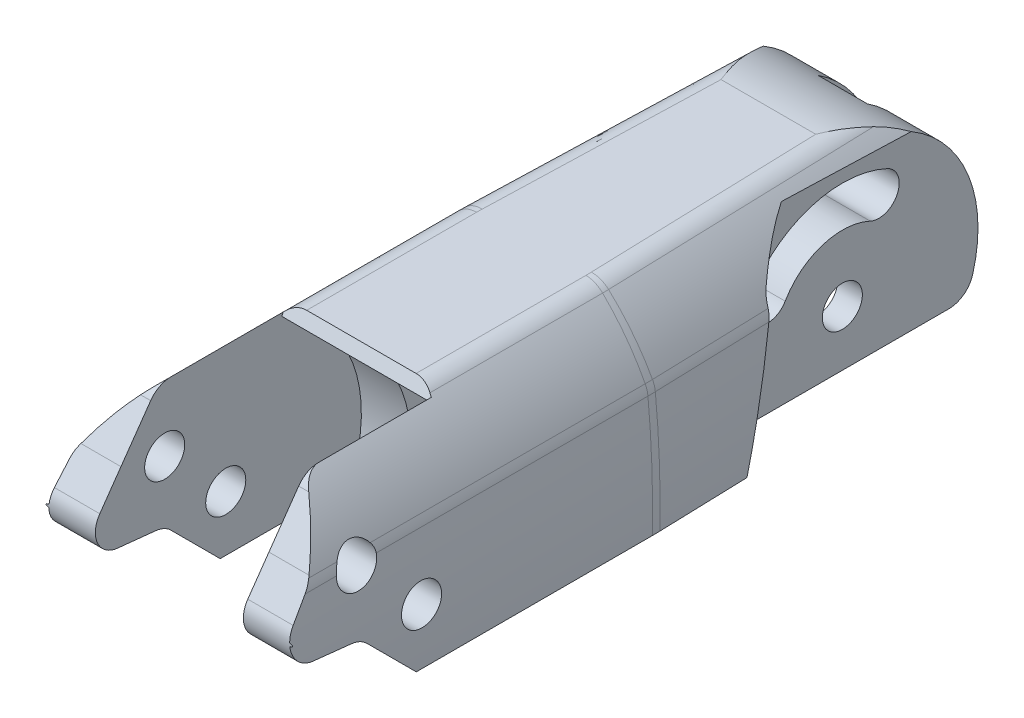
SolidWorks part; units mm, degrees
ref_plane "Front Plane" through (0, 0, 0) normal (0, 0, 1) x (1, 0, 0)
ref_plane "Top Plane" through (0, 0, 0) normal (0, 1, 0) x (1, 0, 0)
ref_plane "Right Plane" through (0, 0, 0) normal (1, 0, 0) x (0, 0, -1)
sketch "Sketch1" plane through (0, 0, 0) normal (1, 0, 0) x (0, 0, -1)
  line L0 (0, 0) -> (-19, 0) construction
  line L1 (-19, 0) -> (-23.9497, 4.9497) construction
  line L2 (19, 11) -> (-22.9449, 11)
  line L3 (-24.5832, 10.1472) -> (-29.2132, 3.5349)
  line L4 (-23.4481, -0.5017) -> (-19.4497, -4.5)
  line L5 (-19.4497, -4.5) -> (27.6458, -4.5)
  line L6 (0, 0) -> (19, 0) construction
  line L7 (19, 0) -> (12.9378, 3.5) construction
  line L8 (21.9583, 6.3442) -> (19, 0) construction
  line L9 (-27.7817, 0.3984) -> (-24.6554, 0.0734)
  circle A0 centre (-19, 0) radius 1.625
  circle A1 centre (19, 0) radius 1.625
  circle A2 centre (-23.9497, 4.9497) radius 1.625
  arc A3 (29.5671, -3.0556) -> (19, 11) centre (19, 0) ccw
  arc A4 (27.6458, -4.5) -> (29.5671, -3.0556) centre (27.6458, -2.5) ccw
  arc A7 (-22.9449, 11) -> (-24.5832, 10.1472) centre (-22.9449, 9) ccw
  circle A8 centre (19, 0) radius 7 construction
  arc A9 (21.261, 4.8487) -> (14.3668, 2.675) centre (19, 0) ccw
  arc A10 (22.6556, 7.8396) -> (11.5089, 4.325) centre (19, 0) ccw
  arc A11 (21.261, 4.8487) -> (22.6556, 7.8396) centre (21.9583, 6.3442) ccw
  arc A12 (11.5089, 4.325) -> (14.3668, 2.675) centre (12.9378, 3.5) ccw
  arc A13 (-23.4481, -0.5017) -> (-24.6554, 0.0734) centre (-24.8623, -1.9159) ccw
  arc A14 (-29.2132, 3.5349) -> (-27.7817, 0.3984) centre (-27.5749, 2.3877) ccw
  point P33 (-23.9497, 0)
  point P36 (-31.1632, 0.75)
  dimension "D1" = 3.25
  dimension "D2" = 3.25
  dimension "D5" = 3.25
  dimension "D8" = 22
  dimension "D14" = 2
  dimension "D15" = 14
  dimension "D16" = 3.3
  dimension "D17" = 1.65
  dimension "D18" = 30
  dimension "D21" = 2
  dimension "D3" = 19
  dimension "D4" = 38
  dimension "D6" = 7
  dimension "D7" = 45
  dimension "D9" = 3.5
  dimension "D10" = 125
  dimension "D11" = 3.5
  dimension "D12" = 4.5
  dimension "D13" = 11
  dimension "D19" = 85
  dimension "D20" = 0.75
extrude "Boss-Extrude1" add sketch "Sketch1" along normal blind 10
sketch "Sketch2" plane through (0, 0, 0) normal (-1, 0, 0) x (0, 0, 1)
  line L0 (-19, 11) -> (-12.5, 11)
  line L1 (-19, 11) -> (22.9449, 11) construction
  line L2 (-12.5, 11) -> (-15, 10.247)
  line L3 (-10.0288, 6.0772) -> (-7.6, -4.5)
  line L4 (19.4497, -4.5) -> (-27.6458, -4.5) construction
  line L5 (-7.6, -4.5) -> (-8.9626, -4.5)
  arc A0 (-19, 11) -> (-8.9626, -4.5) centre (-19, 0) ccw
  arc A1 (-19, 11) -> (-29.5671, -3.0556) centre (-19, 0) ccw construction
  arc A2 (-10.4176, 6.8806) -> (-15, 10.247) centre (-19, 0) ccw
  arc A3 (-10.0288, 6.0772) -> (-10.4176, 6.8806) centre (-11.9781, 5.6296) ccw
  point P17 (-10.1259, 6.5)
  dimension "D1" = 4
  dimension "D5" = 2
  dimension "D2" = 6.5
  dimension "D3" = 6.5
  dimension "D4" = 7.6
extrude "Cut-Extrude1" cut sketch "Sketch2" against normal blind 11 from offset 6 offset against normal yes
sketch "Sketch3" plane through (0, 0, 0) normal (0, 0, 1) x (1, 0, 0)
  line L0 (0, 11) -> (4.4311, 11)
  line L1 (10, 11) -> (0, 11) construction
  line L2 (0, 11) -> (0, 12.0843)
  line L3 (0, 12.0843) -> (12.3003, 12.0843)
  line L4 (12.3003, 12.0843) -> (12.3003, -4.5)
  line L5 (12.3003, -4.5) -> (9.9, -4.5)
  arc A0 (5.8051, 10.4533) -> (9.3121, 5.8612) centre (-6.5613, -2.6261) cw
  arc A1 (9.5389, 5.1132) -> (9.9, -4.5) centre (-70.0795, -2.6912) cw
  arc A2 (9.3121, 5.8612) -> (9.5389, 5.1132) centre (7.5484, 4.9181) cw
  arc A3 (4.4311, 11) -> (5.8051, 10.4533) centre (4.4311, 9) cw
  point P16 (9.5, 5.5)
  point P19 (5.2, 11)
  point P25 (11.1002, -4.5)
  dimension "D1" = 5.2
  dimension "D4" = 18
  dimension "D5" = 80
  dimension "D6" = 2
  dimension "D2" = 5.5
  dimension "D3" = 9.5
  dimension "D7" = 9.9
  dimension "D8" = 4.5
sketch "Sketch11" plane through (0, 0, 0) normal (0, 1, 0) x (1, 0, 0)
  line L0 (10, -29.5749) -> (10, -0.3111)
  line L1 (10, 12.5) -> (10, -22.9449) construction
  line L2 (9.9903, 0.311) -> (9, 32.1338)
  line L3 (9.3121, 0) -> (9.5389, 0) construction
  arc A0 (10, -0.3111) -> (9.9903, 0.311) centre (-10, -0.3111) ccw
  point P14 (10, 0)
  dimension "D1" = 20
  dimension "D2" = 9
sweep "Cut-Sweep1" cut profiles "Sketch3" path "Sketch11"
sketch "Sketch4" plane through (0, 0, 0) normal (1, 0, 0) x (0, 0, -1)
  line L0 (33.5324, 9.2) -> (-30.8909, 9.2)
  line L1 (-30.8909, 9.2) -> (-30.8909, -9.3444)
  line L2 (-30.8909, -9.3444) -> (33.5324, -9.3444)
  line L3 (33.5324, -9.3444) -> (33.5324, 9.2)
  line L4 (19, 11) -> (-22.9449, 11) construction
  dimension "D1" = 1.8
extrude "Cut-Extrude3" cut sketch "Sketch4" along normal blind 2
sketch "Sketch5" plane through (2, 0, 0) normal (-1, 0, 0) x (0, 0, 1)
  line L0 (-35.2245, 0) -> (-23.8541, 0)
  line L1 (-14.1459, 0) -> (14.1459, 0)
  line L2 (23.8541, 0) -> (29.3814, 0)
  line L3 (29.3814, 0) -> (29.3814, -9.8221)
  line L4 (29.3814, -9.8221) -> (-35.2245, -9.8221)
  line L5 (-35.2245, -9.8221) -> (-35.2245, 0)
  arc A0 (-15.9951, 1.2381) -> (-22.0049, 1.2381) centre (-19, 0) ccw
  arc A1 (22.0049, 1.2381) -> (15.9951, 1.2381) centre (19, 0) ccw
  arc A2 (23.8541, 0) -> (22.0049, 1.2381) centre (23.8541, 2) cw
  arc A3 (14.1459, 0) -> (15.9951, 1.2381) centre (14.1459, 2) ccw
  arc A4 (-14.1459, 0) -> (-15.9951, 1.2381) centre (-14.1459, 2) cw
  arc A5 (-23.8541, 0) -> (-22.0049, 1.2381) centre (-23.8541, 2) ccw
  point P15 (22.25, 0)
  point P18 (15.75, 0)
  point P21 (-15.75, 0)
  point P24 (-22.25, 0)
  dimension "D1" = 6.5
  dimension "D2" = 6.5
  dimension "D3" = 2
extrude "Cut-Extrude4" cut sketch "Sketch5" against normal blind 2
mirror "Mirror1" about plane through (0, -2.5, -27.6458) normal (1, 0, 0) of bodies 105
sketch "Sketch10" plane through (0, 0, 0) normal (1, 0, 0) x (0, 0, -1)
  line L0 (-19, 11) -> (-30, 11)
  line L1 (-30, 11) -> (-30, 0)
  line L2 (-14.4482, 10.014) -> (-14, 11)
  line L4 (-14, 11) -> (-19, 11)
  arc A0 (-30, 0) -> (-14.4482, 10.014) centre (-19, 0) ccw
  dimension "D1" = 22
  dimension "D2" = 5
  dimension "D3" = 11
extrude "Cut-Extrude5" cut sketch "Sketch10" against normal mid plane 12
sketch "Sketch12" plane through (0, 0, 0) normal (1, 0, 0) x (0, 0, -1)
  line L0 (-14.3322, 10.2691) -> (-23.451, 10.2691)
  line L1 (-25.088, 9.4181) -> (-27.4966, 5.9864)
  line L2 (-24.5832, 10.1472) -> (-27.5843, 5.8612) construction
  line L3 (-27.4966, 5.9864) -> (-33.6811, 5.9864)
  line L4 (-33.6811, 5.9864) -> (-33.6811, 15.7214)
  line L5 (-33.6811, 15.7214) -> (-14.3322, 15.7214)
  line L6 (-14.3322, 15.7214) -> (-14.3322, 10.2691)
  arc A0 (-23.451, 10.2691) -> (-25.088, 9.4181) centre (-23.451, 8.2691) ccw
  point P12 (-24.4907, 10.2691)
  dimension "D1" = 2
extrude "Cut-Extrude6" cut sketch "Sketch12" against normal through all both and the other way through all
